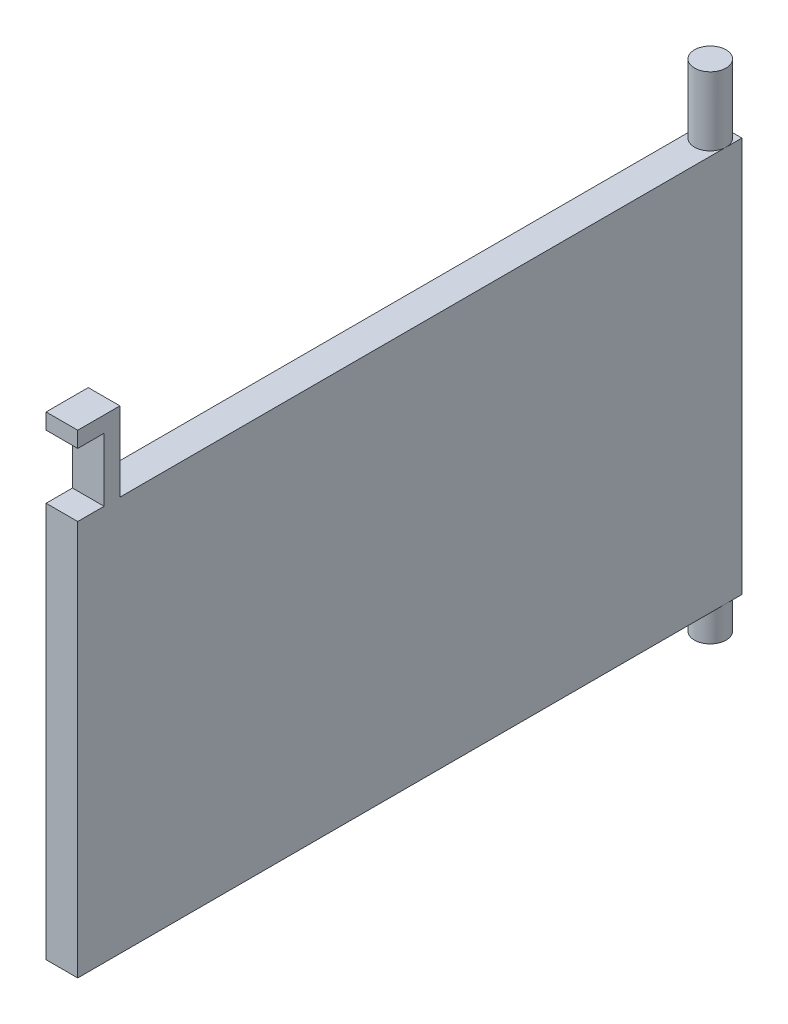
SolidWorks part; units mm, degrees
ref_plane "Přední rovina" through (0, 0, 0) normal (0, 0, 1) x (1, 0, 0)
ref_plane "Horní rovina" through (0, 0, 0) normal (0, 1, 0) x (1, 0, 0)
ref_plane "Pravá rovina" through (0, 0, 0) normal (1, 0, 0) x (0, 0, -1)
sketch "Skica1" plane through (0, 0, 0) normal (0, 0, 1) x (1, 0, 0)
  line L1 (0, 0) -> (6, 0)
  line L2 (0, 0) -> (0, 100)
  line L3 (0, 100) -> (6, 100)
  line L4 (6, 0) -> (6, 100)
  dimension "D1" = 100
  dimension "D2" = 6
extrude "Přidat vysunutím1" add sketch "Skica1" along normal blind 6
sketch "Skica4" plane through (0, 100, 0) normal (0, 1, 0) x (1, 0, 0)
  line L0 (6, 0) -> (0, 0) construction
  line L1 (6, -6) -> (6, 0) construction
  circle A0 centre (3, -3) radius 3
  dimension "D2" = 6
  dimension "D3" = 3
  dimension "D1" = 3
extrude "Odebrat vysunutím3" cut sketch "Skica4" against normal blind 15 flip side to cut contours A0
sketch "Skica6" plane through (0, 0, 0) normal (0, -1, 0) x (1, 0, 0)
  line L0 (0, 6) -> (6, 6) construction
  line L1 (0, 6) -> (0, 0) construction
  circle A0 centre (3, 3) radius 3
  dimension "D1" = 6
  dimension "D2" = 3
  dimension "D3" = 3
extrude "Odebrat vysunutím4" cut sketch "Skica6" against normal blind 10 flip side to cut
sketch "Skica7" plane through (0, 0, 0) normal (0, -1, 0) x (1, 0, 0)
  circle A0 centre (3, 3) radius 3
extrude "Odebrat vysunutím5" cut sketch "Skica7" against normal blind 5
sketch "Skica10" plane through (0, 5, 0) normal (0, -1, 0) x (1, 0, 0)
  circle A0 centre (3, 3) radius 3
extrude "Přidat vysunutím2" add sketch "Skica10" along normal blind 1
sketch "Skica11" plane through (0, 0, 6) normal (0, 0, 1) x (1, 0, 0)
  line L1 (0, 85) -> (6, 85)
  line L2 (0, 85) -> (0, 10)
  line L3 (0, 10) -> (6, 10)
  line L4 (6, 85) -> (6, 10)
extrude "Přidat vysunutím3" add sketch "Skica11" along normal blind 120
sketch "Skica14" plane through (0, 100, 0) normal (0, 1, 0) x (1, 0, 0)
  circle A0 centre (3, -3) radius 3
extrude "Odebrat vysunutím8" cut sketch "Skica14" against normal blind 2
sketch "Skica19" plane through (0, 85, 0) normal (0, 1, 0) x (1, 0, 0)
  line L0 (0, -3) -> (0, -126) construction
  line L1 (0, -118) -> (6, -118)
  line L2 (0, -118) -> (0, -121)
  line L3 (0, -121) -> (6, -121)
  line L4 (6, -118) -> (6, -121)
  line L5 (6, -126) -> (6, -3) construction
  line L6 (6, -126) -> (0, -126) construction
  dimension "D1" = 3
  dimension "D2" = 5
extrude "Přidat vysunutím6" add sketch "Skica19" along normal blind 15
sketch "Skica20" plane through (0, 0, 121) normal (0, 0, 1) x (1, 0, 0)
  line L0 (6, 100) -> (6, 85) construction
  line L1 (0, 100) -> (6, 100)
  line L2 (0, 100) -> (0, 97)
  line L3 (0, 97) -> (6, 97)
  line L4 (6, 100) -> (6, 97)
  dimension "D1" = 3
extrude "Přidat vysunutím8" add sketch "Skica20" along normal blind 5
